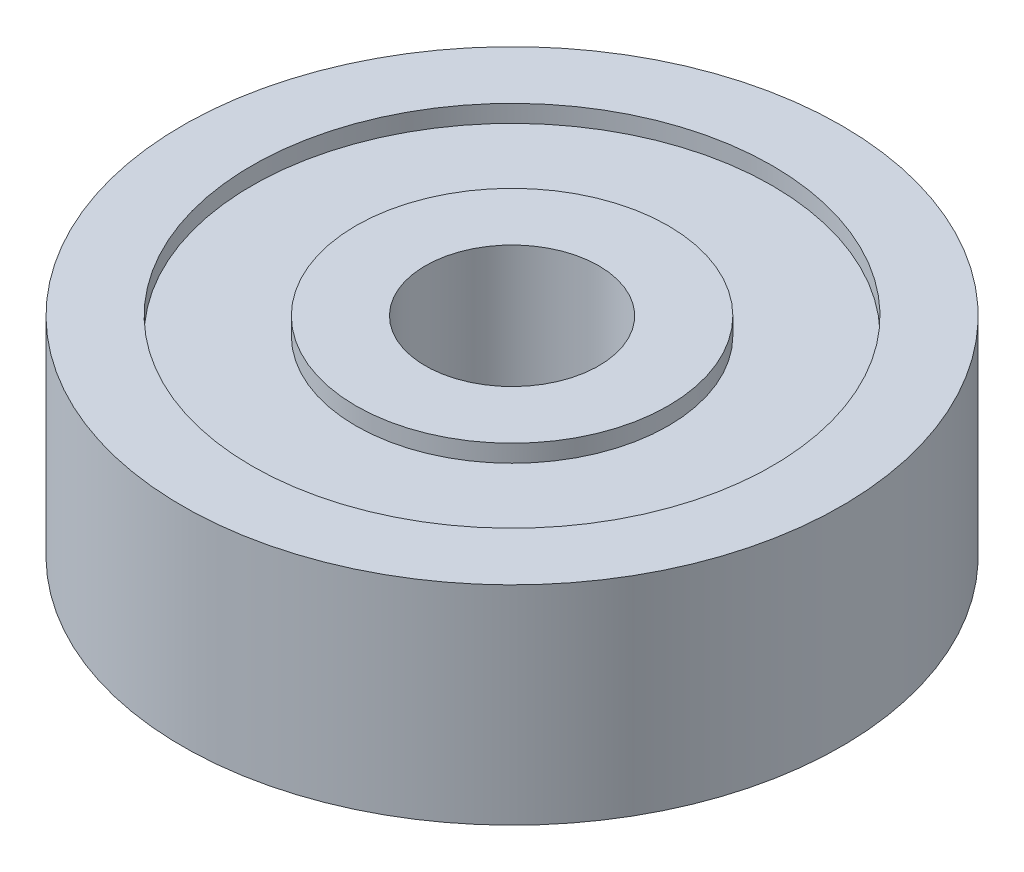
SolidWorks part; units mm, degrees
material "合金钢"
ref_plane "前视基准面" through (0, 0, 0) normal (0, 0, 1) x (1, 0, 0)
ref_plane "上视基准面" through (0, 0, 0) normal (0, 1, 0) x (1, 0, 0)
ref_plane "右视基准面" through (0, 0, 0) normal (1, 0, 0) x (0, 0, -1)
sketch "草图1" plane through (0, 0, 0) normal (0, 0, 1) x (1, 0, 0)
  line L0 (0, 0) -> (0, 6) construction
  line L1 (2.5, 0) -> (2.5, 6)
  line L2 (2.5, 6) -> (4.5, 6)
  line L3 (4.5, 6) -> (4.5, 5.5)
  line L4 (4.5, 5.5) -> (7.5, 5.5)
  line L5 (7.5, 5.5) -> (7.5, 6)
  line L6 (7.5, 6) -> (9.5, 6)
  line L7 (9.5, 6) -> (9.5, 0)
  line L8 (9.5, 0) -> (7.5, 0)
  line L9 (7.5, 0) -> (7.5, 0.5)
  line L10 (7.5, 0.5) -> (4.5, 0.5)
  line L11 (4.5, 0.5) -> (4.5, 0)
  line L12 (4.5, 0) -> (2.5, 0)
  point P9 (9.5, 0)
  point P16 (6.9724, 0)
  dimension "D1" = 6
  dimension "D2" = 5
  dimension "D3" = 19
  dimension "D4" = 0.5
  dimension "D5" = 2
revolve "旋转1" add sketch "草图1" angle 360 about L0
